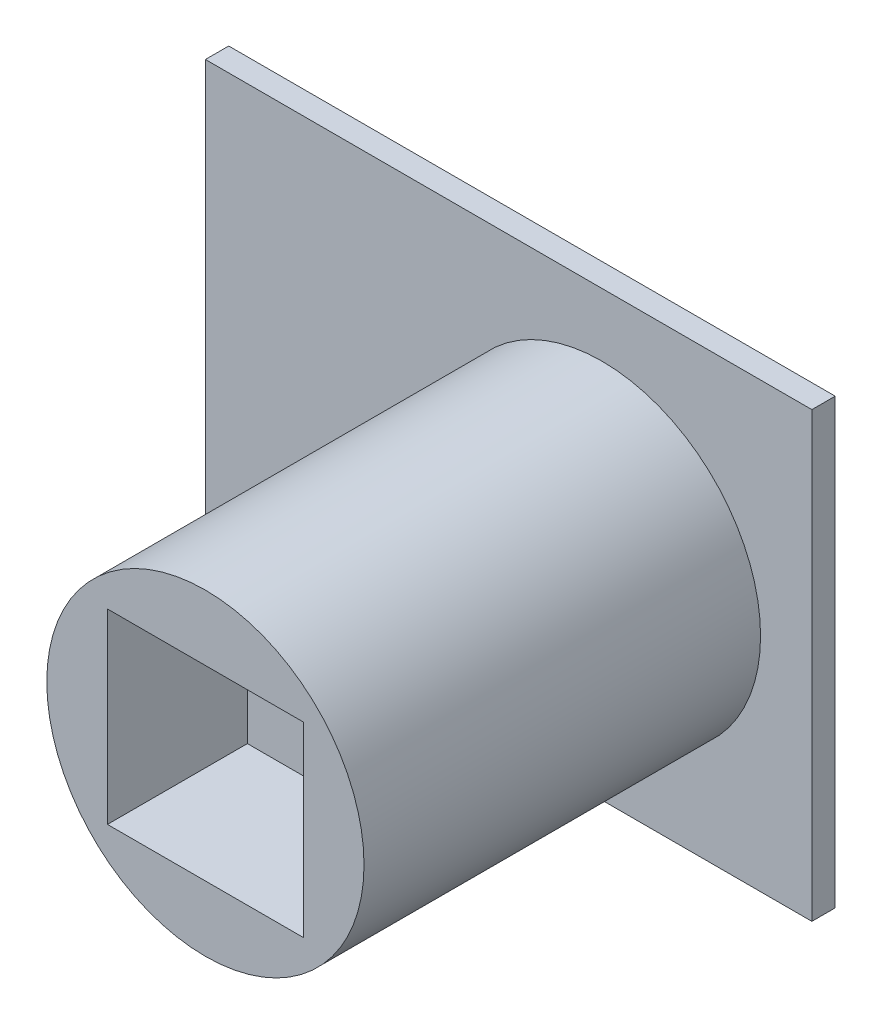
SolidWorks part; units mm, degrees
ref_plane "Alzado" through (0, 0, 0) normal (0, 0, 1) x (1, 0, 0)
ref_plane "Planta" through (0, 0, 0) normal (0, 1, 0) x (1, 0, 0)
ref_plane "Vista lateral" through (0, 0, 0) normal (1, 0, 0) x (0, 0, -1)
sketch "Croquis1" plane through (0, 0, 0) normal (0, 0, 1) x (1, 0, 0)
  line L1 (-65, -47.5) -> (65, -47.5)
  line L2 (-65, -47.5) -> (-65, 47.5)
  line L3 (-65, 47.5) -> (65, 47.5)
  line L4 (65, -47.5) -> (65, 47.5)
  line L5 (-65, -47.5) -> (65, 47.5) construction
  line L6 (-65, 47.5) -> (65, -47.5) construction
  point P0 (0, 0)
  dimension "D1" = 130
  dimension "D2" = 95
extrude "Saliente-Extruir1" add sketch "Croquis1" along normal blind 5
sketch "Croquis2" plane through (0, 0, 5) normal (0, 0, 1) x (1, 0, 0)
  line L0 (0, 0) -> (20, 0) construction
  circle A0 centre (20, 0) radius 34
  dimension "D2" = 68
  dimension "20" = 20
extrude "Saliente-Extruir2" add sketch "Croquis2" along normal blind 85
sketch "Croquis3" plane through (0, 0, 90) normal (0, 0, 1) x (1, 0, 0)
  line L1 (-1, -20) -> (41, -20)
  line L2 (-1, -20) -> (-1, 20)
  line L3 (-1, 20) -> (41, 20)
  line L4 (41, -20) -> (41, 20)
  line L5 (-1, -20) -> (41, 20) construction
  line L6 (-1, 20) -> (41, -20) construction
  point P0 (20, 0)
  dimension "D1" = 42
  dimension "D2" = 40
extrude "Cortar-Extruir1" cut sketch "Croquis3" against normal blind 30
